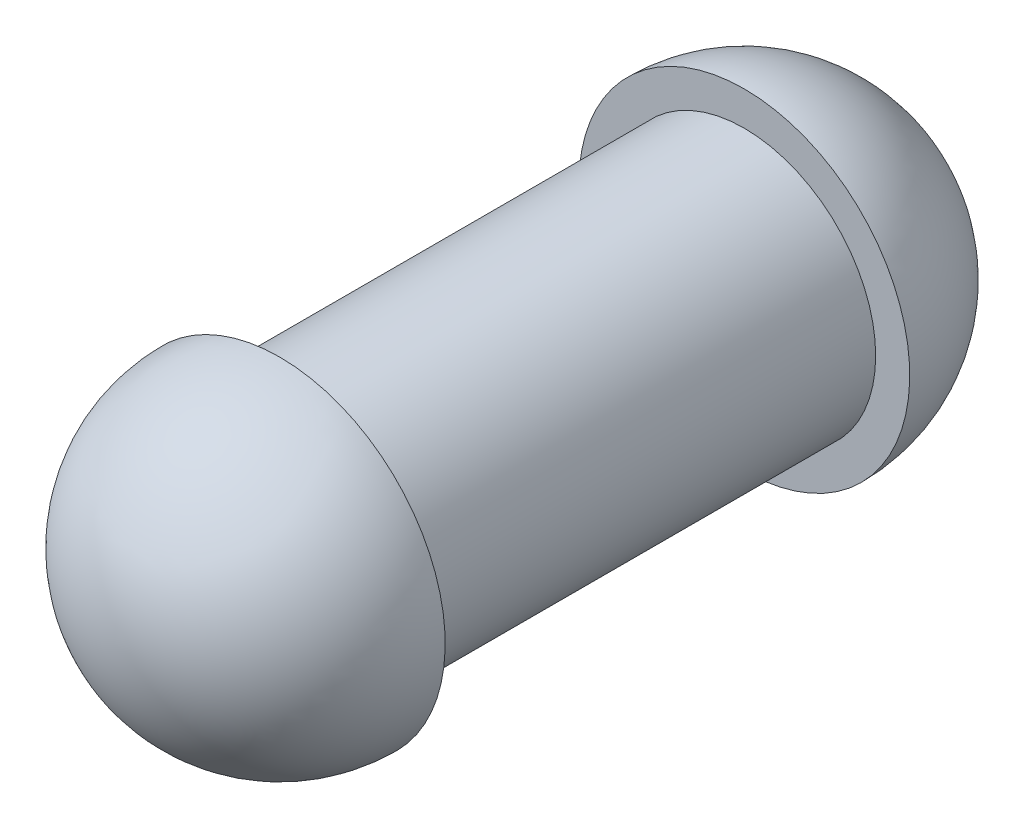
SolidWorks part; units mm, degrees
ref_plane "Front Plane" through (0, 0, 0) normal (0, 0, 1) x (1, 0, 0)
ref_plane "Top Plane" through (0, 0, 0) normal (0, 1, 0) x (1, 0, 0)
ref_plane "Right Plane" through (0, 0, 0) normal (1, 0, 0) x (0, 0, -1)
sketch "Sketch1" plane through (0, 0, 0) normal (0, 0, 1) x (1, 0, 0)
  circle A0 centre (0, 0) radius 20.65
  dimension "D1" = 41.3
extrude "Boss-Extrude1" add sketch "Sketch1" along normal mid plane 73
sketch "Sketch2" plane through (0, 0, 0) normal (1, 0, 0) x (0, 0, -1)
  line L0 (0, 0) -> (-63.0026, 0) construction
  line L1 (-36.5, 20.65) -> (-36.5, -20.65) construction
  line L2 (-62.5, 0) -> (-36.5, 0)
  line L3 (-36.5, 0) -> (-36.5, 26)
  arc A0 (-36.5, 26) -> (-62.5, 0) centre (-36.5, 0) ccw
  dimension "D1" = 26
revolve "Revolve1" add sketch "Sketch2" angle 360 about L0
mirror "Mirror1" about plane through (0, 0, 0) normal (0, 0, 1) of bodies 102
